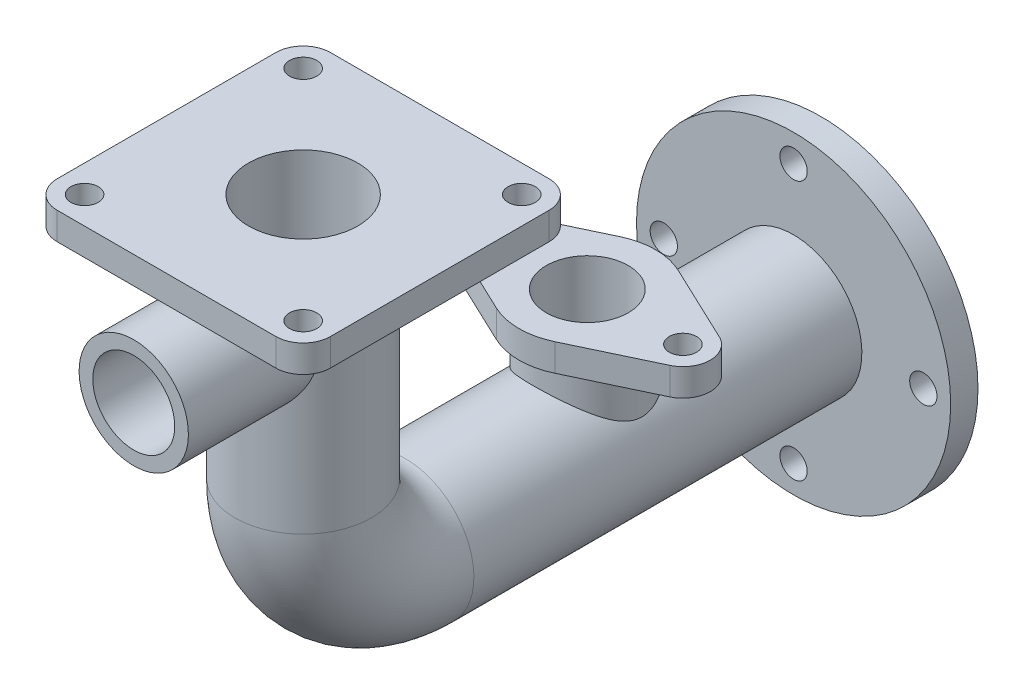
SolidWorks part; units mm, degrees
ref_plane "Front Plane" through (0, 0, 0) normal (0, 0, 1) x (1, 0, 0)
ref_plane "Top Plane" through (0, 0, 0) normal (0, 1, 0) x (1, 0, 0)
ref_plane "Right Plane" through (0, 0, 0) normal (1, 0, 0) x (0, 0, -1)
sketch "Sketch1" plane through (0, 0, 0) normal (0, 0, 1) x (1, 0, 0)
  circle A0 centre (0, 0) radius 12.5
  circle A1 centre (0, 0) radius 10
  dimension "D1" = 25
  dimension "D2" = 20
sketch "Sketch2" plane through (0, 0, 0) normal (1, 0, 0) x (0, 0, -1)
  line L0 (0, 0) -> (-76, 0)
  line L1 (-94.75, 18.75) -> (-94.75, 63.75)
  arc A0 (-76, 0) -> (-94.75, 18.75) centre (-76, 18.75) cw
  dimension "D3" = 18.75
  dimension "D1" = 76
  dimension "D2" = 45
sweep "Sweep1" add profiles "Sketch1" path "Sketch2"
sketch "Sketch3" plane through (0, 0, 0) normal (0, 0, -1) x (-1, 0, 0)
  circle A0 centre (0, 0) radius 28.75
  circle A1 centre (0, 0) radius 10 construction
  circle A2 centre (0, 0) radius 10
  dimension "D1" = 57.5
extrude "Boss-Extrude1" add sketch "Sketch3" against normal blind 5
hole_wizard "Hole1" positions "Sketch6" profile "Sketch7" legacy
sketch "Sketch6" plane through (0, 0, 5) normal (0, 0, 1) x (1, 0, 0)
  point P0 (23.75, 0)
  point P4 (0, 0)
  dimension "D1" = 23.75
sketch "Sketch7" plane through (23.75, 0, 5) normal (1, 0, 0) x (0, -1, 0)
  line L0 (0, 0) -> (0, 5)
  line L1 (0, 5) -> (2.5, 5)
  line L2 (2.5, 5) -> (2.5, 0)
  line L3 (2.5, 0) -> (0, 0)
  line L4 (0, 110) -> (0, -10) construction
  dimension "Diameter" = 5
  dimension "Depth" = 5
pattern_circular "CirPattern1" count 4 over 360 about axis through (0, 0, 0) along (0, 0, 1) of "Hole1"
sketch "Sketch8" plane through (0, 63.75, 0) normal (0, 1, 0) x (1, 0, 0)
  line L1 (-25, -69.75) -> (25, -69.75)
  line L2 (-25, -69.75) -> (-25, -119.75)
  line L3 (-25, -119.75) -> (25, -119.75)
  line L4 (25, -69.75) -> (25, -119.75)
  line L5 (-25, -69.75) -> (25, -119.75) construction
  line L6 (-25, -119.75) -> (25, -69.75) construction
  circle A0 centre (0, -94.75) radius 10 construction
  circle A1 centre (0, -94.75) radius 10
  point P0 (0, -94.75)
  dimension "D1" = 50
  dimension "D2" = 50
extrude "Boss-Extrude3" add sketch "Sketch8" against normal blind 5
fillet "Fillet1" radius 5 4 edges at (-25, 61.25, 69.75) (25, 61.25, 69.75) (-25, 61.25, 119.75) (25, 61.25, 119.75)
hole_wizard "Hole2" positions "Sketch9" profile "Sketch10" legacy end condition up to next
sketch "Sketch9" plane through (0, 63.75, 0) normal (0, 1, 0) x (1, 0, 0)
  point P0 (20, -74.75)
  point P3 (-20, -74.75)
  point P6 (20, -114.75)
  point P9 (-20, -114.75)
sketch "Sketch10" plane through (20, 63.75, 74.75) normal (1, 0, 0) x (0, 0, 1)
  line L0 (0, 0) -> (0, 5)
  line L1 (0, 5) -> (2.5, 5)
  line L2 (2.5, 5) -> (2.5, 0)
  line L3 (2.5, 0) -> (0, 0)
  line L4 (0, 110) -> (0, -10) construction
  dimension "Diameter" = 5
  dimension "Depth" = 5
ref_plane "Plane1" through (0, 22.75, 0) normal (0, 1, 0) x (1, 0, 0)
sketch "Sketch11" plane through (0, 22.75, 0) normal (0, 1, 0) x (1, 0, 0)
  line L0 (0, -94.75) -> (0, -42.75) construction
  line L1 (-19.6429, -38.2325) -> (-5.3571, -31.4562)
  line L2 (19.6429, -38.2325) -> (5.3571, -31.4562)
  line L3 (0, -42.75) -> (26.9873, -42.75) construction
  line L4 (19.6429, -47.2675) -> (5.3571, -54.0438)
  line L5 (-19.6429, -47.2675) -> (-5.3571, -54.0438)
  circle A0 centre (0, -42.75) radius 7.5
  arc A1 (5.3571, -31.4562) -> (-5.3571, -31.4562) centre (0, -42.75) ccw
  arc A2 (-19.6429, -38.2325) -> (-19.6429, -47.2675) centre (-17.5, -42.75) ccw
  arc A3 (19.6429, -47.2675) -> (19.6429, -38.2325) centre (17.5, -42.75) ccw
  arc A4 (-5.3571, -54.0438) -> (5.3571, -54.0438) centre (0, -42.75) ccw
  point P2 (-88.8838, -28.9885)
  dimension "D1" = 10
  dimension "D2" = 25
  dimension "D3" = 15
  dimension "D4" = 52
  dimension "D5" = 35
  dimension "D6" = 17.5
extrude "Boss-Extrude4" add sketch "Sketch11" against normal blind 5 separate body
sketch "Sketch12" plane through (0, 22.75, 0) normal (0, 1, 0) x (1, 0, 0)
  circle A1 centre (0, -42.75) radius 10
  dimension "D1" = 20
extrude "Boss-Extrude5" add sketch "Sketch12" against normal up to next
sketch "Sketch15" plane through (0, 22.75, 0) normal (0, 1, 0) x (1, 0, 0)
  circle A0 centre (0, -42.75) radius 7.5
  dimension "D1" = 15
extrude "Cut-Extrude1" cut sketch "Sketch15" against normal up to next
hole_wizard "Hole4" positions "Sketch16" profile "Sketch17" legacy end condition up to next
sketch "Sketch16" plane through (0, 22.75, 0) normal (0, 1, 0) x (1, 0, 0)
  point P0 (17.5, -42.75)
  point P3 (-17.5, -42.75)
sketch "Sketch17" plane through (17.5, 22.75, 42.75) normal (1, 0, 0) x (0, 0, 1)
  line L0 (0, 0) -> (0, 5)
  line L1 (0, 5) -> (2.5, 5)
  line L2 (2.5, 5) -> (2.5, 0)
  line L3 (2.5, 0) -> (0, 0)
  line L4 (0, 110) -> (0, -10) construction
  dimension "Diameter" = 5
  dimension "Depth" = 5
ref_plane "Plane2" through (0, 0, 94.75) normal (0, 0, -1) x (-1, 0, 0)
ref_plane "Plane3" through (0, 0, 125.75) normal (0, 0, -1) x (-1, 0, 0)
sketch "Sketch19" plane through (0, 0, 125.75) normal (0, 0, -1) x (-1, 0, 0)
  circle A0 centre (0, 46.25) radius 10
  circle A1 centre (0, 46.25) radius 7.5
  point P3 (0, 0)
  dimension "D1" = 20
  dimension "D2" = 15
  dimension "D3" = 46.25
extrude "Boss-Extrude6" add sketch "Sketch19" along normal up to next
